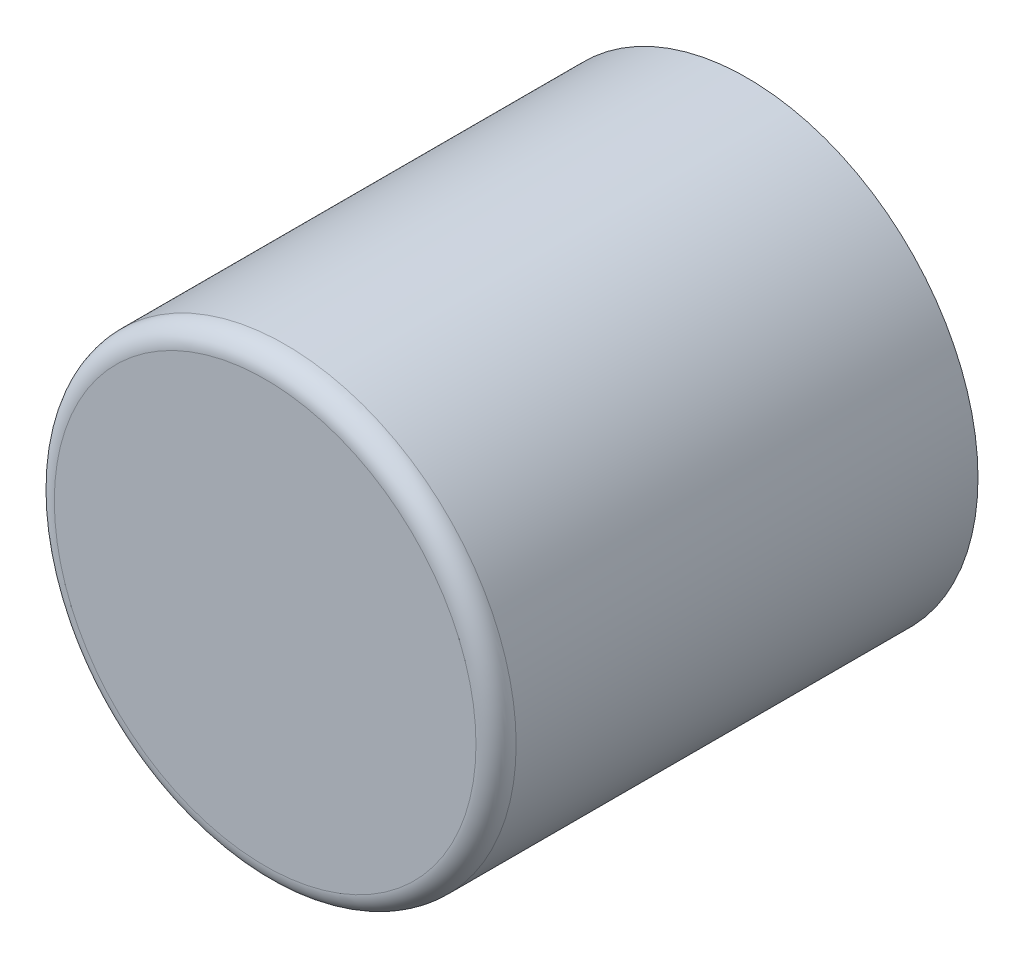
SolidWorks part; units mm, degrees
material "ﾎﾟﾘ塩化ﾋﾞﾆﾙ(PVC)硬質"
ref_plane "正面" through (0, 0, 0) normal (0, 0, 1) x (1, 0, 0)
ref_plane "平面" through (0, 0, 0) normal (0, 1, 0) x (1, 0, 0)
ref_plane "右側面" through (0, 0, 0) normal (1, 0, 0) x (0, 0, -1)
sketch "ｽｹｯﾁ1" plane through (0, 0, 0) normal (0, 0, 1) x (1, 0, 0)
  circle A0 centre (0, 0) radius 23
  dimension "D1" = 46
extrude "ﾎﾞｽ - 押し出し1" add sketch "ｽｹｯﾁ1" along normal blind 48
sketch "ｽｹｯﾁ2" plane through (0, 0, 0) normal (0, 0, -1) x (-1, 0, 0)
  circle A0 centre (0, 0) radius 19
  dimension "D1" = 38
extrude "ｶｯﾄ - 押し出し1" cut sketch "ｽｹｯﾁ2" against normal blind 44
fillet "ﾌｨﾚｯﾄ1" radius 2 1 edges at (23, 0, 48)
